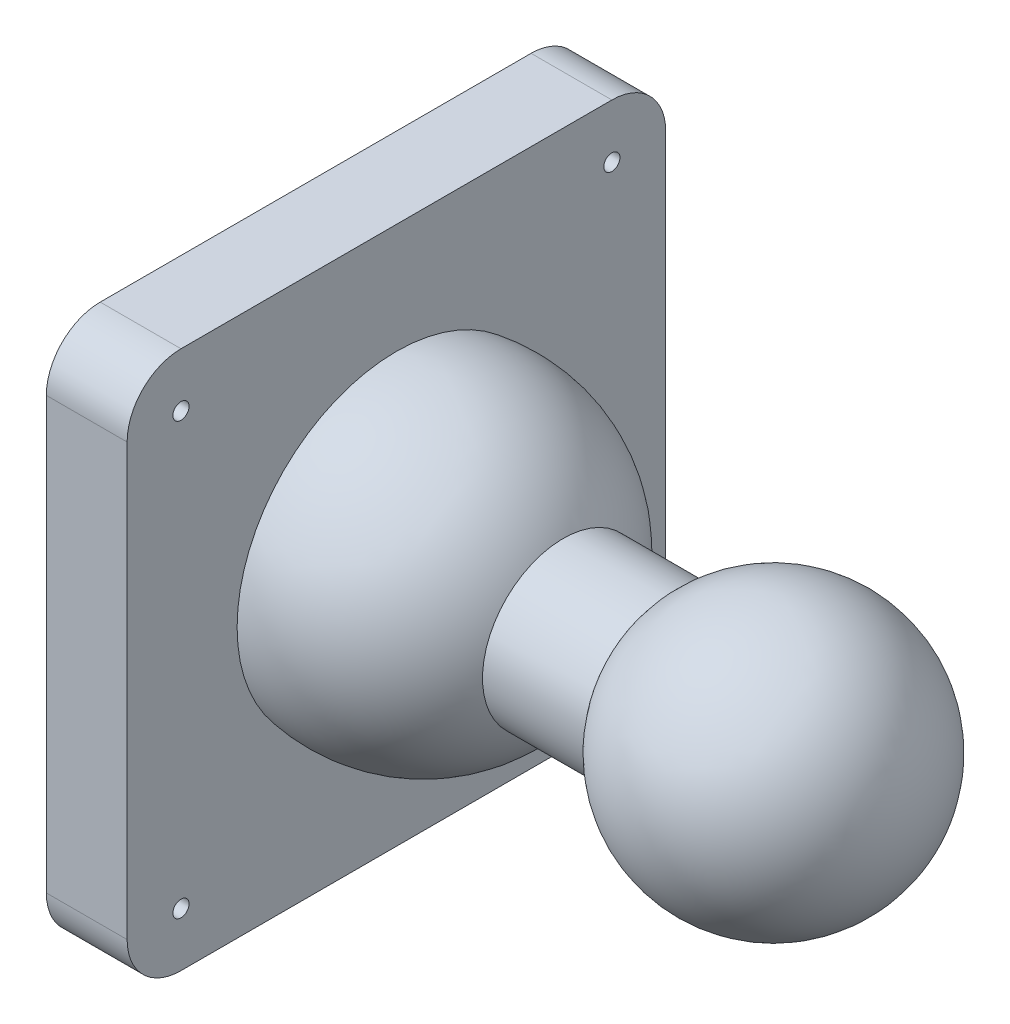
SolidWorks part; units mm, degrees
ref_plane "Alzado" through (0, 0, 0) normal (0, 0, 1) x (1, 0, 0)
ref_plane "Planta" through (0, 0, 0) normal (0, 1, 0) x (1, 0, 0)
ref_plane "Vista lateral" through (0, 0, 0) normal (1, 0, 0) x (0, 0, -1)
sketch "Croquis2" plane through (0, 0, 0) normal (0, 1, 0) x (1, 0, 0)
  line L2 (0, 0) -> (25, 0) construction
  line L3 (0, 25) -> (0, 0)
  arc A0 (25, 0) -> (0, 25) centre (0, 0) ccw
  dimension "D1" = 50
revolve "Revolución-Lámina1" add sketch "Croquis2" angle 360 about L2
sketch "Croquis4" plane through (-5, 0, 0) normal (-1, 0, 0) x (0, 0, 1)
  circle A0 centre (0, 0) radius 15
  dimension "D1" = 30
extrude "Saliente-Extruir2" add sketch "Croquis4" against normal blind 10 and the other way up to surface from offset 40 offset against normal yes
sketch "Croquis5" plane through (0, 0, 0) normal (0, 1, 0) x (1, 0, 0)
  line L0 (0, 0) -> (45, 0) construction
  line L1 (45, -15) -> (45, 15) construction
  line L2 (45, 0) -> (45, 15)
  line L3 (45, 0) -> (90, 0) construction
  line L4 (45, 0) -> (90, 0)
  arc A0 (90, 0) -> (45, 15) centre (65, 0) ccw
  dimension "D2" = 50
  dimension "D1" = 20
revolve "Revolución1" add sketch "Croquis5" angle 360 about L3
sketch "Croquis6" plane through (-5, 0, 0) normal (-1, 0, 0) x (0, 0, 1)
  line L1 (-50, -50) -> (50, -50)
  line L2 (-50, -50) -> (-50, 50)
  line L3 (-50, 50) -> (50, 50)
  line L4 (50, -50) -> (50, 50)
  line L5 (-50, -50) -> (50, 50) construction
  line L6 (-50, 50) -> (50, -50) construction
  point P0 (0, 0)
  dimension "D1" = 100
  dimension "D2" = 100
extrude "Saliente-Extruir3" add sketch "Croquis6" along normal blind 15
fillet "Redondeo1" radius 10 4 edges at (-12.5, 50, -50) (-12.5, 50, 50) (-12.5, -50, -50) (-12.5, -50, 50)
sketch "Croquis7" plane through (-5, 0, 0) normal (1, 0, 0) x (0, 0, -1)
  line L0 (0, 0) -> (0, 40) construction
  line L1 (0, 0) -> (43.7956, 0) construction
  circle A0 centre (-40, 40) radius 1.5
  circle A1 centre (40, 40) radius 1.5
  circle A2 centre (40, -40) radius 1.5
  circle A3 centre (-40, -40) radius 1.5
  dimension "D1" = 3
extrude "Cortar-Extruir1" cut sketch "Croquis7" against normal blind 15
